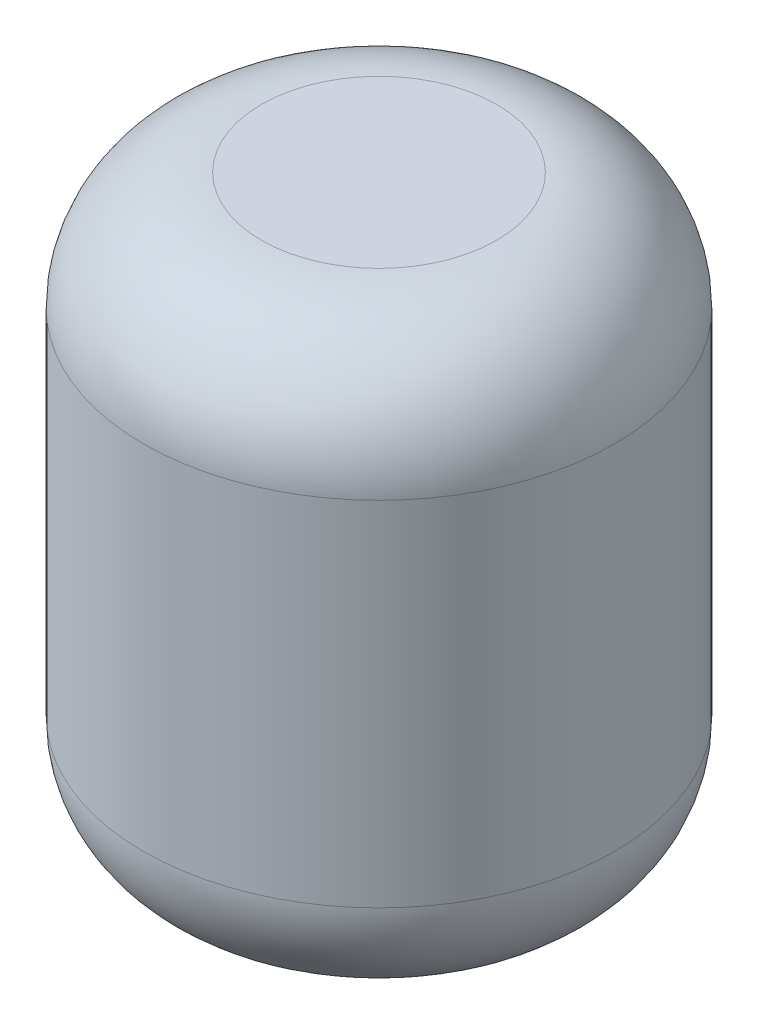
SolidWorks part; units mm, degrees
ref_plane "Front Plane" through (0, 0, 0) normal (0, 0, 1) x (1, 0, 0)
ref_plane "Top Plane" through (0, 0, 0) normal (0, 1, 0) x (1, 0, 0)
ref_plane "Right Plane" through (0, 0, 0) normal (1, 0, 0) x (0, 0, -1)
sketch "Sketch1" plane through (0, 0, 0) normal (0, 1, 0) x (1, 0, 0)
  circle A0 centre (0, 0) radius 50.8
  dimension "D1" = 101.6
extrude "Boss-Extrude1" add sketch "Sketch1" along normal blind 127
fillet "Fillet1" radius 25.4 1 edges at (0, 127, 50.8)
fillet "Fillet2" radius 25.4 1 edges at (0, 0, 50.8)
